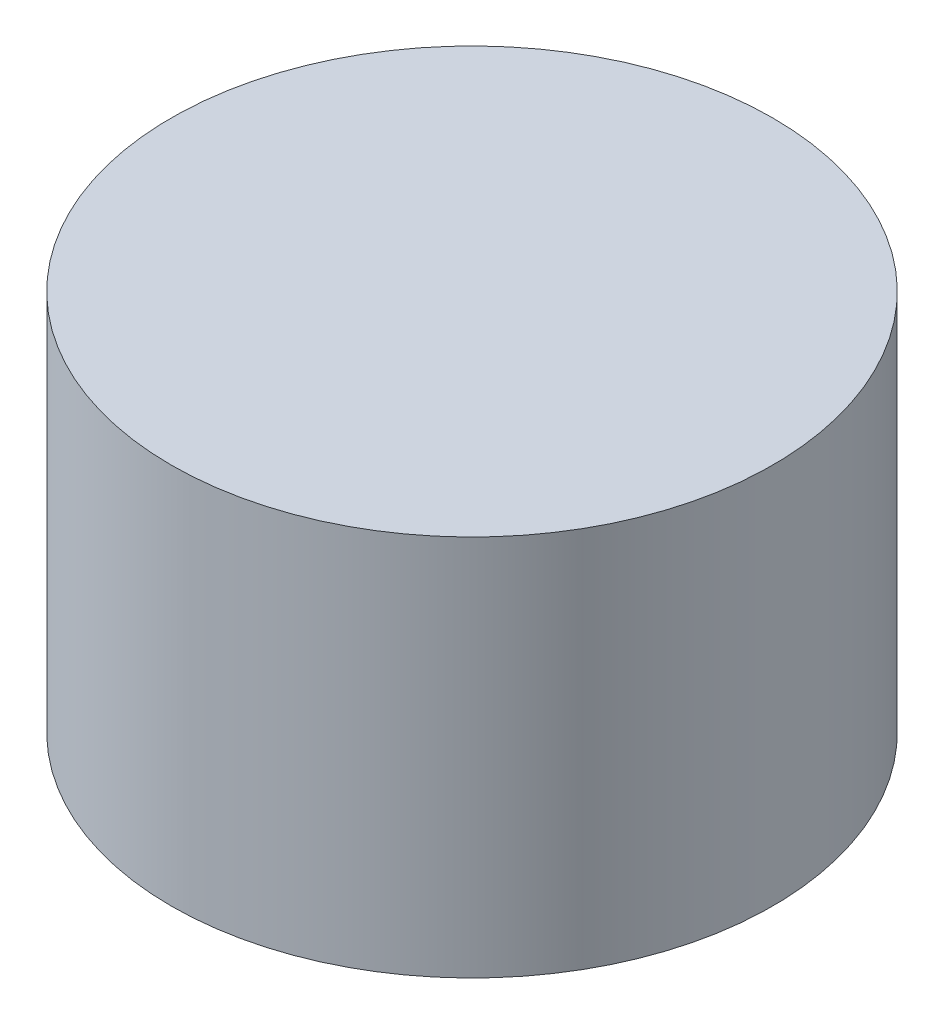
SolidWorks part; units mm, degrees
ref_plane "Front Plane" through (0, 0, 0) normal (0, 0, 1) x (1, 0, 0)
ref_plane "Top Plane" through (0, 0, 0) normal (0, 1, 0) x (1, 0, 0)
ref_plane "Right Plane" through (0, 0, 0) normal (1, 0, 0) x (0, 0, -1)
sketch "Sketch1" plane through (0, 0, 0) normal (0, 1, 0) x (1, 0, 0)
  circle A0 centre (0, 0) radius 2.5
  dimension "D1" = 5
extrude "Boss-Extrude1" add sketch "Sketch1" along normal blind 3.175
